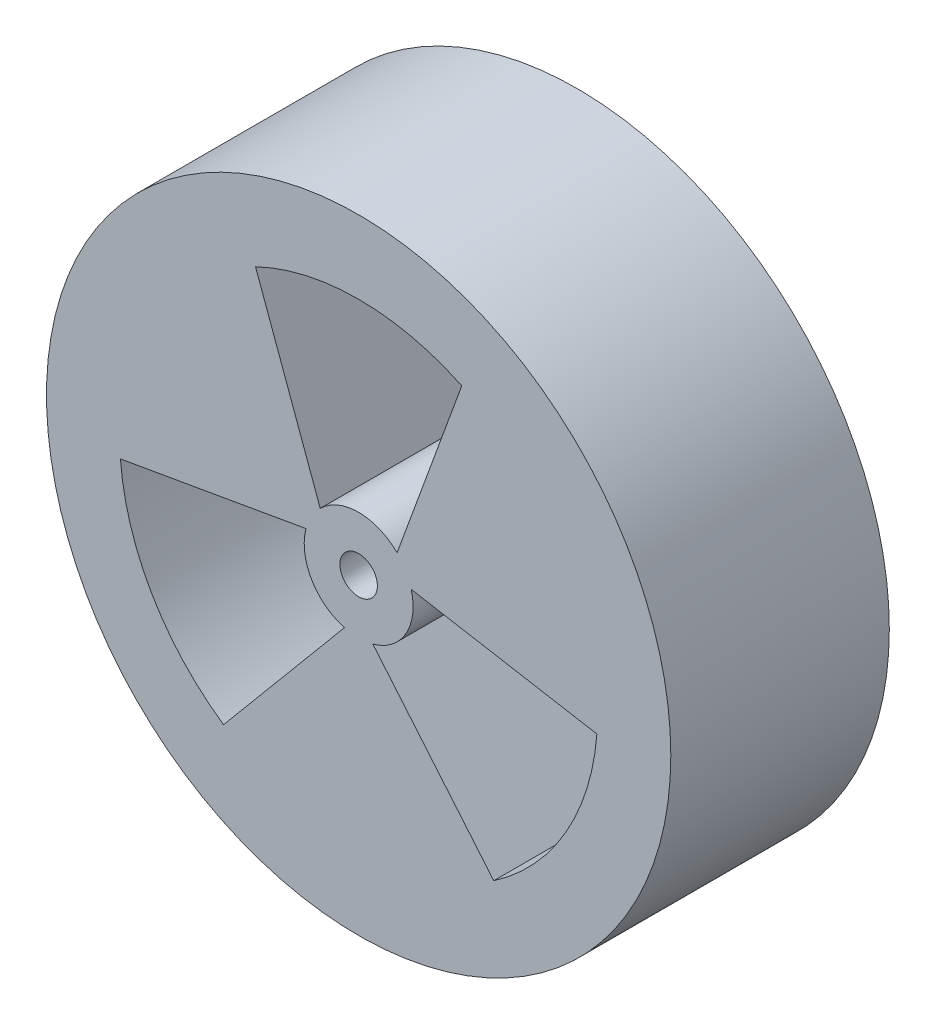
SolidWorks part; units mm, degrees
ref_plane "Front Plane" through (0, 0, 0) normal (0, 0, 1) x (1, 0, 0)
ref_plane "Top Plane" through (0, 0, 0) normal (0, 1, 0) x (1, 0, 0)
ref_plane "Right Plane" through (0, 0, 0) normal (1, 0, 0) x (0, 0, -1)
sketch "Sketch1" plane through (0, 0, 0) normal (0, 0, 1) x (1, 0, 0)
  circle A0 centre (0, 0) radius 50
  circle A1 centre (0, 0) radius 3
  dimension "D1" = 100
extrude "Boss-Extrude1" add sketch "Sketch1" along normal blind 35
sketch "Sketch3" plane through (0, 0, 35) normal (0, 0, 1) x (1, 0, 0)
  line L0 (0, 38.2722) -> (0, 8.7229)
  line L1 (-6.1553, 6.1807) -> (-16.519, 34.5237)
  arc A0 (-6.1553, 6.1807) -> (0, 8.7229) centre (0, 0) cw
  arc A2 (-16.519, 34.5237) -> (0, 38.2722) centre (0, 0) cw
  dimension "D1" = 0
extrude "Cut-Extrude1" cut sketch "Sketch3" against normal blind 35
mirror "Mirror1" about plane through (0, 38.2722, 0) normal (1, 0, 0) of "Cut-Extrude1"
pattern_circular "CirPattern6" count 3 over 360 about axis through (0, 0, 0) along (0, 0, 1) of "Cut-Extrude1"
mirror "Mirror2" about plane through (33.1447, -19.1361, 0) normal (-0.5, -0.866, 0) of "CirPattern6", "Cut-Extrude1"
